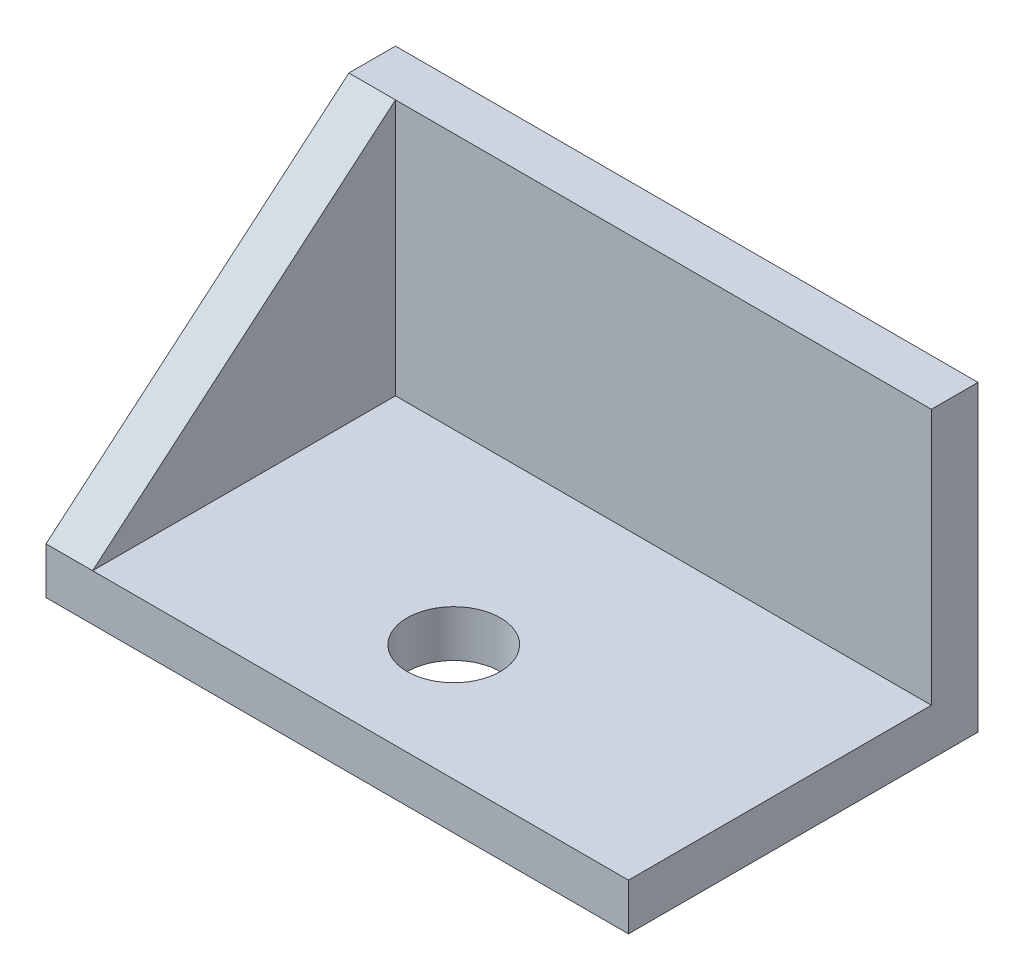
SolidWorks part; units mm, degrees
ref_plane "Front Plane" through (0, 0, 0) normal (0, 0, 1) x (1, 0, 0)
ref_plane "Top Plane" through (0, 0, 0) normal (0, 1, 0) x (1, 0, 0)
ref_plane "Right Plane" through (0, 0, 0) normal (1, 0, 0) x (0, 0, -1)
sketch "Sketch1" plane through (0, 0, 0) normal (1, 0, 0) x (0, 0, -1)
  line L1 (0, 0) -> (-75, 0)
  line L2 (0, 0) -> (0, 65)
  line L3 (0, 65) -> (-10, 65)
  line L4 (-75, 0) -> (-75, 10)
  line L6 (-75, 10) -> (-10, 65)
  dimension "D1" = 10
  dimension "D2" = 10
  dimension "D3" = 75
  dimension "D4" = 65
extrude "Boss-Extrude1" add sketch "Sketch1" along normal blind 125
sketch "Sketch2" plane through (125, 0, 0) normal (1, 0, 0) x (0, 0, -1)
  line L1 (-75, 10) -> (-10, 10)
  line L2 (-75, 10) -> (-75, 65)
  line L3 (-75, 65) -> (-10, 65)
  line L4 (-10, 10) -> (-10, 65)
extrude "Cut-Extrude1" cut sketch "Sketch2" against normal blind 115
hole_wizard "Hole1" positions "Sketch3" profile "Sketch4" legacy end condition through all
sketch "Sketch3" plane through (0, 10, 0) normal (0, 1, 0) x (1, 0, 0)
  line L0 (125, -75) -> (125, -10) construction
  line L1 (125, -75) -> (10, -75) construction
  point P0 (62.5, -50)
  dimension "D1" = 62.5
  dimension "D2" = 25
sketch "Sketch4" plane through (62.5, 10, 50) normal (1, 0, 0) x (0, 0, 1)
  line L0 (0, 0) -> (0, 10)
  line L1 (0, 10) -> (10, 10)
  line L2 (10, 10) -> (10, 0)
  line L3 (10, 0) -> (0, 0)
  line L4 (0, 110) -> (0, -10) construction
  dimension "Diameter" = 20
  dimension "Depth" = 10
